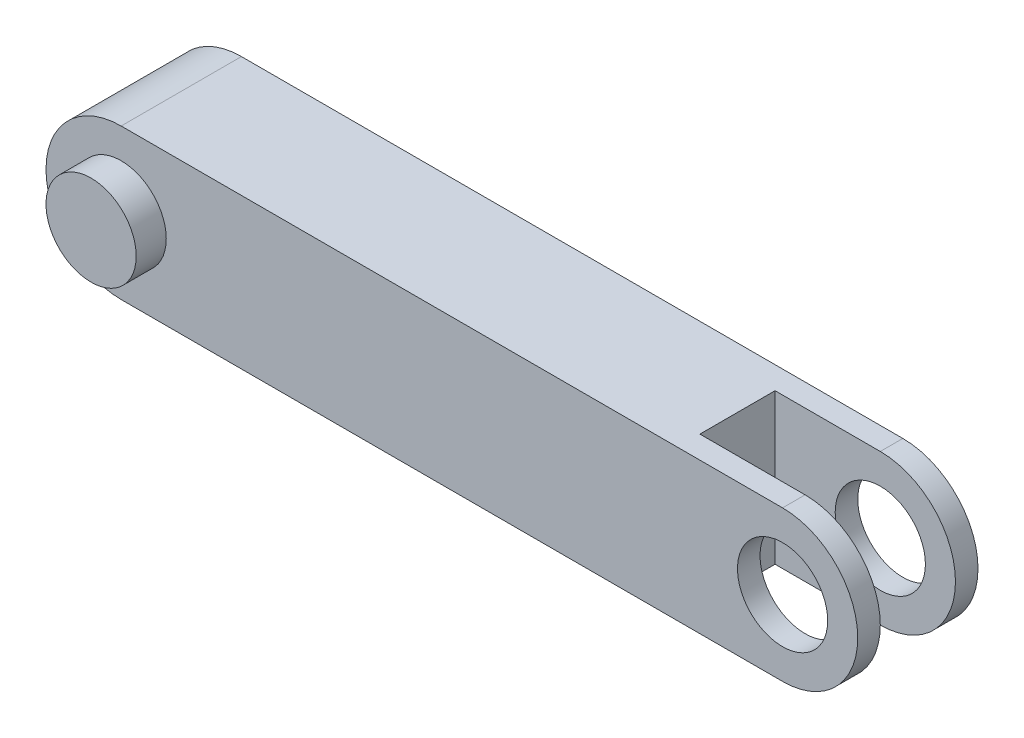
SolidWorks part; units mm, degrees
material "1023 Carbon Steel Sheet (SS)"
ref_plane "Front Plane" through (0, 0, 0) normal (0, 0, 1) x (1, 0, 0)
ref_plane "Top Plane" through (0, 0, 0) normal (0, 1, 0) x (1, 0, 0)
ref_plane "Right Plane" through (0, 0, 0) normal (1, 0, 0) x (0, 0, -1)
sketch "Sketch1" plane through (0, 0, 0) normal (0, 0, 1) x (1, 0, 0)
  line L0 (-55.5037, 0) -> (164.4963, 0) construction
  line L1 (-55.5037, 25) -> (164.4963, 25)
  line L2 (-55.5037, -25) -> (164.4963, -25)
  arc A0 (-55.5037, 25) -> (-55.5037, -25) centre (-55.5037, 0) ccw
  arc A1 (164.4963, -25) -> (164.4963, 25) centre (164.4963, 0) ccw
  point P3 (54.4963, 0)
  dimension "D1" = 50
  dimension "D2" = 220
extrude "Boss-Extrude1" add sketch "Sketch1" along normal blind 40
sketch "Sketch3" plane through (0, 0, 40) normal (0, 0, 1) x (1, 0, 0)
  circle A2 centre (-55.5037, 0) radius 15
extrude "Boss-Extrude2" add sketch "Sketch3" along normal blind 10 contours A2
sketch "Sketch4" plane through (0, 0, 0) normal (0, 0, -1) x (-1, 0, 0)
  circle A2 centre (55.5037, 0) radius 15
extrude "Boss-Extrude3" add sketch "Sketch4" along normal blind 10
sketch "Sketch5" plane through (0, 25, 0) normal (0, 1, 0) x (1, 0, 0)
  line L0 (189.4963, -40) -> (189.4963, 0) construction
  line L1 (129.4963, -7.5) -> (189.4963, -7.5)
  line L2 (129.4963, -7.5) -> (129.4963, -32.5)
  line L3 (129.4963, -32.5) -> (189.4963, -32.5)
  line L4 (189.4963, -7.5) -> (189.4963, -32.5)
  dimension "D1" = 60
  dimension "D2" = 25
extrude "Cut-Extrude1" cut sketch "Sketch5" against normal through all
sketch "Sketch6" plane through (0, 0, 40) normal (0, 0, 1) x (1, 0, 0)
  circle A2 centre (164.4963, 0) radius 15
extrude "Cut-Extrude2" cut sketch "Sketch6" against normal through all
